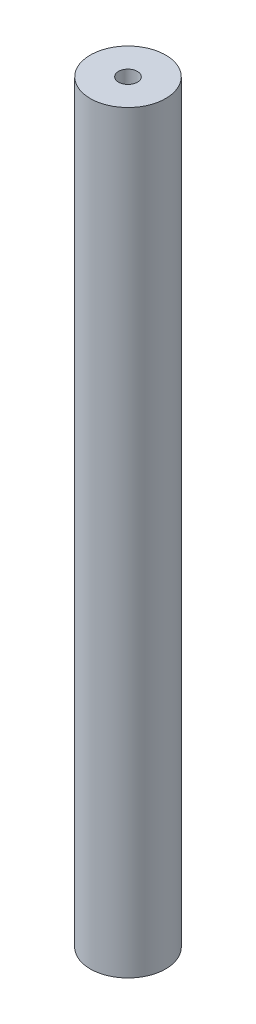
SolidWorks part; units mm, degrees
ref_plane "Front Plane" through (0, 0, 0) normal (0, 0, 1) x (1, 0, 0)
ref_plane "Top Plane" through (0, 0, 0) normal (0, 1, 0) x (1, 0, 0)
ref_plane "Right Plane" through (0, 0, 0) normal (1, 0, 0) x (0, 0, -1)
sketch "Sketch1" plane through (0, 0, 0) normal (0, 1, 0) x (1, 0, 0)
  circle A0 centre (0, 0) radius 25.4
  dimension "D1" = 50.8
extrude "Boss-Extrude1" add sketch "Sketch1" along normal blind 508
sketch "Sketch2" plane through (0, 508, 0) normal (0, 1, 0) x (1, 0, 0)
  circle A0 centre (0, 0) radius 6.35
extrude "Cut-Extrude1" cut sketch "Sketch2" against normal blind 508
